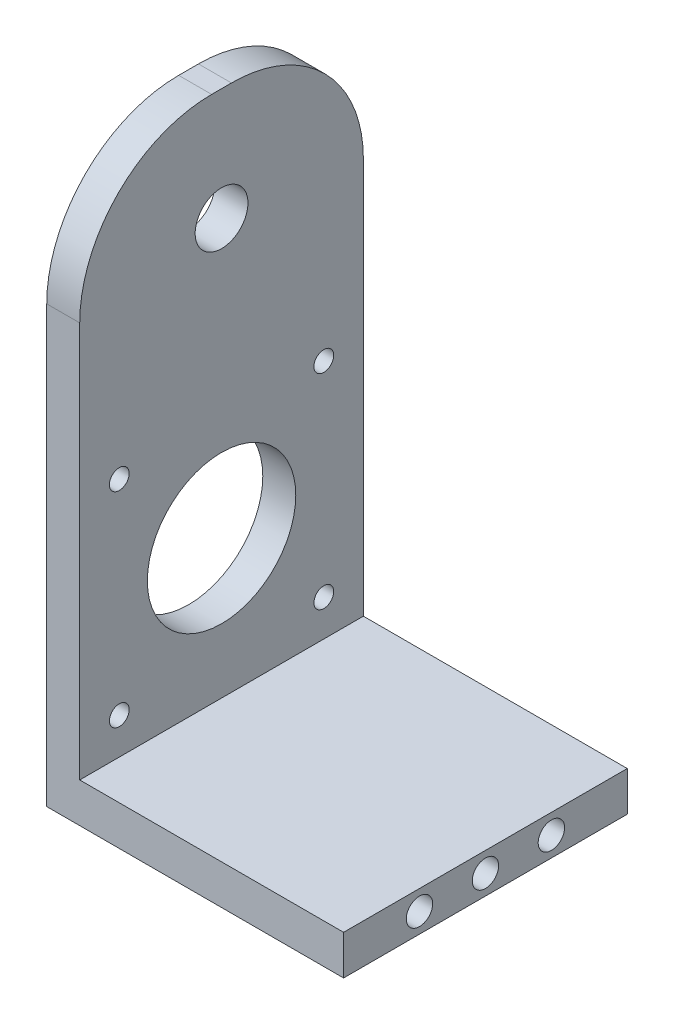
SolidWorks part; units mm, degrees
ref_plane "Front Plane" through (0, 0, 0) normal (0, 0, 1) x (1, 0, 0)
ref_plane "Top Plane" through (0, 0, 0) normal (0, 1, 0) x (1, 0, 0)
ref_plane "Right Plane" through (0, 0, 0) normal (1, 0, 0) x (0, 0, -1)
sketch "Sketch1" plane through (0, 0, 0) normal (0, 1, 0) x (1, 0, 0)
  line L1 (22.5, -21.5) -> (-22.5, -21.5)
  line L2 (22.5, -21.5) -> (22.5, 21.5)
  line L3 (22.5, 21.5) -> (-22.5, 21.5)
  line L4 (-22.5, -21.5) -> (-22.5, 21.5)
  line L5 (22.5, -21.5) -> (-22.5, 21.5) construction
  line L6 (22.5, 21.5) -> (-22.5, -21.5) construction
  point P0 (0, 0)
  dimension "D1" = 43
  dimension "D2" = 45
extrude "Boss-Extrude1" add sketch "Sketch1" along normal blind 6
sketch "Sketch2" plane through (0, 6, 0) normal (0, 1, 0) x (1, 0, 0)
  line L0 (-22.5, 21.5) -> (-22.5, -21.5)
  line L1 (-22.5, 21.5) -> (-17.5, 21.5)
  line L2 (-22.5, -21.5) -> (-17.5, -21.5)
  line L3 (-17.5, 21.5) -> (-17.5, -21.5)
  dimension "D1" = 5
extrude "Boss-Extrude2" add sketch "Sketch2" along normal blind 80
sketch "Sketch3" plane through (-17.5, 0, 0) normal (1, 0, 0) x (0, 0, -1)
  line L0 (0, 0) -> (0, 27) construction
  line L1 (-21.5, 6) -> (21.5, 6) construction
  line L2 (21.5, 27) -> (-21.5, 27) construction
  line L3 (-21.5, 86) -> (-21.5, 6) construction
  circle A0 centre (0, 27) radius 11.25
  circle A1 centre (-15.5, 42.5) radius 1.5
  circle A2 centre (15.5, 42.5) radius 1.5
  circle A3 centre (15.5, 11.5) radius 1.5
  circle A4 centre (-15.5, 11.5) radius 1.5
  point P11 (0, 27)
  point P22 (0, 27)
  dimension "D2" = 22.5
  dimension "D3" = 3
  dimension "D1" = 21
  dimension "D4" = 31
  dimension "D5" = 31
  dimension "D6" = 4
extrude "Cut-Extrude1" cut sketch "Sketch3" against normal up to next
sketch "Sketch4" plane through (-17.5, 0, 0) normal (1, 0, 0) x (0, 0, -1)
  line L0 (0, 0) -> (0, 86) construction
  line L1 (-21.5, 86) -> (21.5, 86) construction
  circle A0 centre (0, 27) radius 11.25 construction
  circle A1 centre (0, 27) radius 11.25 construction
  circle A2 centre (0, 69) radius 4
  dimension "D1" = 8
  dimension "D2" = 42
extrude "Cut-Extrude2" cut sketch "Sketch4" against normal up to next
fillet "Fillet1" radius 20 2 edges at (-20, 86, 21.5) (-20, 86, -21.5)
sketch "Sketch6" plane through (22.5, 0, 0) normal (1, 0, 0) x (0, 0, -1)
  line L0 (-21.5, 3) -> (21.5, 3) construction
  line L1 (-21.5, 6) -> (-21.5, 0) construction
  line L2 (21.5, 6) -> (21.5, 0) construction
  circle A0 centre (0, 3) radius 2
  circle A1 centre (10, 3) radius 2
  circle A2 centre (-10, 3) radius 2
  dimension "D1" = 4
  dimension "D2" = 21.5
  dimension "D3" = 2
  dimension "D4" = 2
extrude "Cut-Extrude4" cut sketch "Sketch6" against normal blind 10
